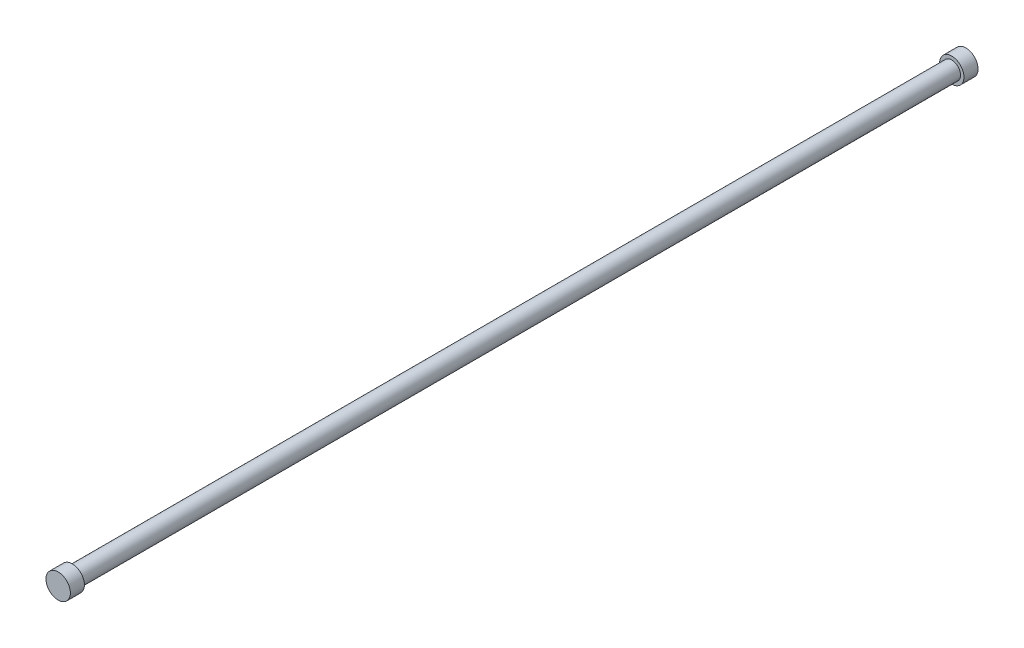
SolidWorks part; units mm, degrees
ref_plane "Front Plane" through (0, 0, 0) normal (0, 0, 1) x (1, 0, 0)
ref_plane "Top Plane" through (0, 0, 0) normal (0, 1, 0) x (1, 0, 0)
ref_plane "Right Plane" through (0, 0, 0) normal (1, 0, 0) x (0, 0, -1)
sketch "Sketch1" plane through (0, 0, 0) normal (0, 0, 1) x (1, 0, 0)
  circle A0 centre (0, 0) radius 3.175
extrude "Boss-Extrude1" add sketch "Sketch1" along normal blind 317.5
sketch "Sketch2" plane through (0, 0, 0) normal (0, 0, -1) x (-1, 0, 0)
  circle A0 centre (0, 0) radius 4.4017
extrude "Boss-Extrude2" add sketch "Sketch2" along normal blind 5.08
sketch "Sketch3" plane through (0, 0, 317.5) normal (0, 0, 1) x (1, 0, 0)
  circle A0 centre (0, 0) radius 4.4017
extrude "Boss-Extrude3" add sketch "Sketch3" along normal blind 5.08
